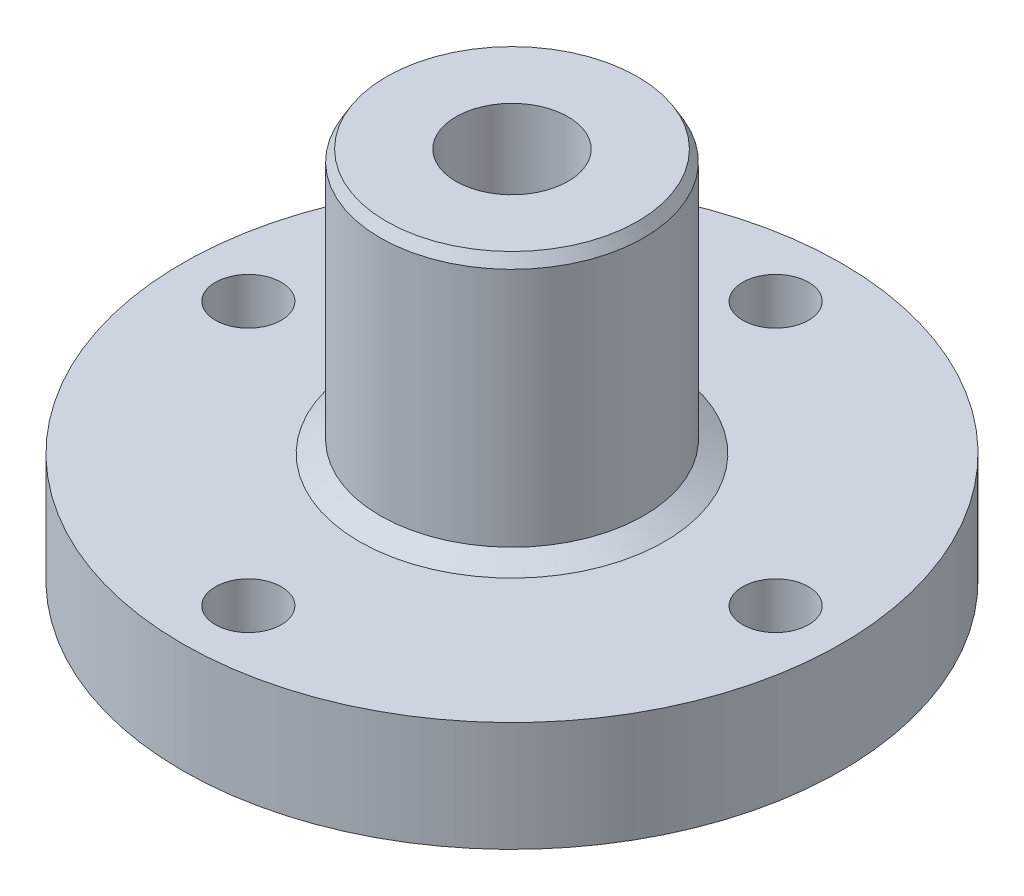
SolidWorks part; units mm, degrees
ref_plane "前视基准面" through (0, 0, 0) normal (0, 0, 1) x (1, 0, 0)
ref_plane "上视基准面" through (0, 0, 0) normal (0, 1, 0) x (1, 0, 0)
ref_plane "右视基准面" through (0, 0, 0) normal (1, 0, 0) x (0, 0, -1)
sketch "草图1" plane through (0, 0, 0) normal (0, 1, 0) x (1, 0, 0)
  circle A0 centre (0, 0) radius 15
  dimension "D1" = 30
extrude "凸台-拉伸1" add sketch "草图1" along normal blind 5
sketch "草图2" plane through (0, 5, 0) normal (0, 1, 0) x (1, 0, 0)
  circle A0 centre (0, 0) radius 12 construction
  point P4 (0, 12)
  point P6 (0, -12)
  point P8 (-12, 0)
  point P10 (12, 0)
  dimension "D1" = 24
sketch "草图4" plane through (0, 5, 0) normal (0, 1, 0) x (1, 0, 0)
  circle A0 centre (0, 0) radius 6
  dimension "D1" = 12
extrude "凸台-拉伸2" add sketch "草图4" along normal blind 12
sketch "草图5" plane through (0, 17, 0) normal (0, 1, 0) x (1, 0, 0)
  circle A0 centre (0, 0) radius 2.55
  dimension "D1" = 5.1
extrude "切除-拉伸1" cut sketch "草图5" against normal through all
sketch "草图6" plane through (0, 0, 0) normal (0, 0, 1) x (1, 0, 0)
  line L0 (-2, 10) -> (2, 10)
  line L1 (2, 10) -> (2, 13)
  line L2 (2, 13) -> (-2, 13)
  line L3 (0, 13) -> (0, 10) construction
  line L5 (2.55, 17) -> (-2.55, 17) construction
  line L7 (-2, 10) -> (-2, 13)
  dimension "D1" = 2
  dimension "D2" = 3
  dimension "D3" = 4
extrude "切除-拉伸2" cut sketch "草图6" against normal through all
chamfer "倒角1" distance 0.947 angle 30 1 edges at (0, 5, 6)
chamfer "倒角2" distance 0.5 angle 30 1 edges at (0, 17, 6)
sketch "草图7" plane through (0, 5, 0) normal (0, 1, 0) x (1, 0, 0)
  circle A0 centre (0, 12) radius 1.5
  circle A1 centre (-12, 0) radius 1.5
  circle A2 centre (12, 0) radius 1.5
  circle A3 centre (0, -12) radius 1.5
  dimension "D1" = 3
  dimension "D2" = 3
  dimension "D3" = 3
  dimension "D4" = 3
extrude "切除-拉伸3" cut sketch "草图7" against normal through all
